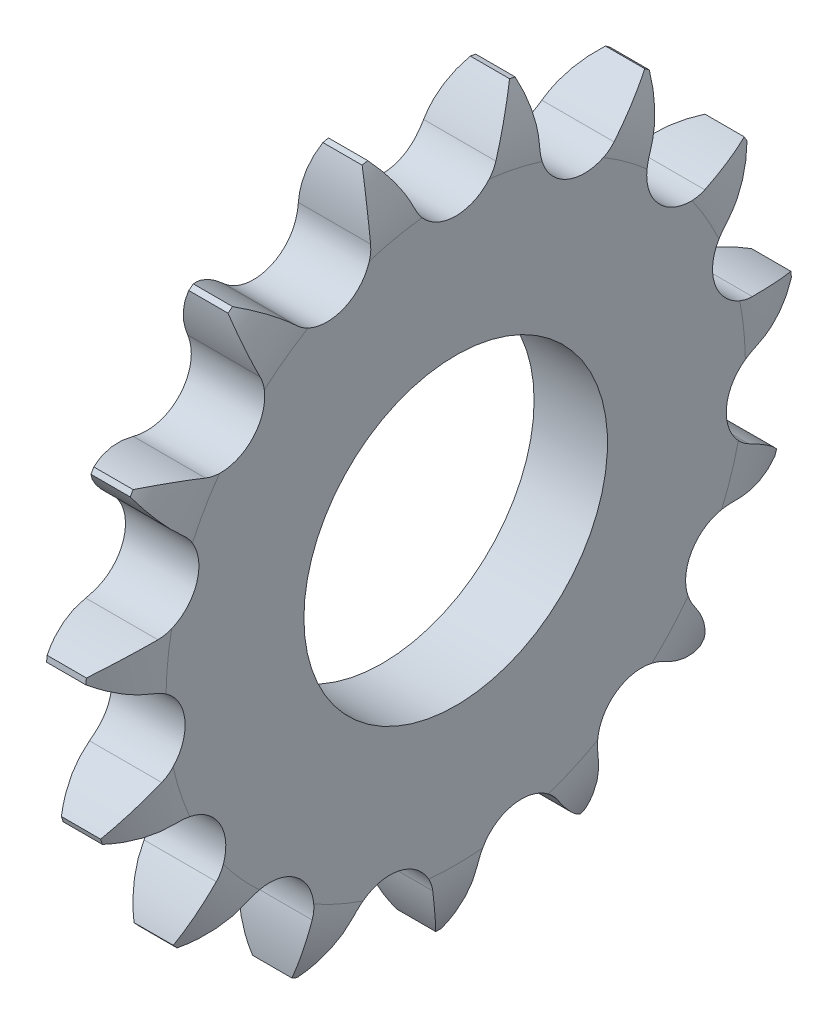
SolidWorks part; units mm, degrees
ref_plane "Plane1" through (0, 0, 0) normal (0, 0, 1) x (1, 0, 0)
ref_plane "Plane2" through (0, 0, 0) normal (0, 1, 0) x (1, 0, 0)
ref_plane "Plane3" through (0, 0, 0) normal (1, 0, 0) x (0, 0, -1)
sketch "Clipboard" plane through (0, 0, 0) normal (0, 1, 0) x (1, 0, 0)
  line L0 (0, 0) -> (9.2004, -2.4653)
  line L1 (-15, 0) -> (100, 0) construction
  line L2 (0, 0) -> (-0.8203, 0.9272)
  line L3 (0, 0) -> (-8.8973, 3.4006)
  line L4 (0, 0) -> (2.9944, 0.8023)
  line L5 (0, 0) -> (-46.8476, -17.4728)
  line L6 (0, 0) -> (-4.4098, -2.9753)
  line L7 (-0.8203, 0.9272) -> (47.2432, 14.7092)
  line L8 (-76.2, 38.1) -> (-72.9, 38.1)
  line L9 (-73.3242, 40.7328) -> (-72.926, 40.7699)
  line L10 (-73.4529, 9.1872) -> (-63.2129, 9.1872)
  circle A0 centre (0, 0) radius 3.175
  circle A1 centre (0, 0) radius 17.7306
  circle A2 centre (0, 0) radius 37.5
  dimension "Dr" = 6.35
  dimension "MHD" = 35.4612
  dimension "Hub_dia" = 75
  dimension "Num_teeth" = 15
  dimension "Pitch" = 9.525
  dimension "Width" = 3.1
  dimension "Side_relief" = 1.238
  dimension "Side_radius" = 9.525
  dimension "Overall_len" = 50
  dimension "Show_teeth" = 15
  dimension "Thickness" = 5.3196
  dimension "OAL" = 50.0005
  dimension "T_dim" = 3.3
  dimension "Fillet_rad" = 0.4
  dimension "Face_width" = 5.32
  dimension "Num_strands" = 1
  dimension "Transv_pitch" = 10.24
  dimension "Plate_wid" = 8.26
sketch "BasProSke" plane through (0, 0, 0) normal (0, 1, 0) x (1, 0, 0)
  line L0 (-10, 0) -> (60, 0) construction
  line L1 (0, 0) -> (0, 20.9886)
  line L2 (0, 0) -> (5.3196, 0)
  line L3 (5.3196, 0) -> (5.3196, 20.9886)
  line L4 (4.0816, 25.6845) -> (1.238, 25.6845)
  arc A0 (0, 20.9886) -> (1.238, 25.6845) centre (9.525, 20.9886) cw
  arc A1 (5.3196, 20.9886) -> (4.0816, 25.6845) centre (-4.2054, 20.9886) ccw
  dimension "Thickness" = 5.3196
  dimension "D1" = 9.525
  dimension "G1" = 1.238
  dimension "G2" = 1.238
  dimension "Diameter" = 51.369
revolve "Base-Revolve" add sketch "BasProSke" angle 360 about L0
sketch "TooCutSke" plane through (0, 0, 0) normal (1, 0, 0) x (0, 0, -1)
  line L0 (0, 22.9381) -> (2.9518, 21.6851) construction
  line L1 (0, 0) -> (0, 107) construction
  line L2 (0, 22.9381) -> (-10, 22.9381) construction
  line L3 (0, 22.9381) -> (-2.9518, 21.6851) construction
  arc A0 (2.9518, 21.6851) -> (5.5304, 25.5938) centre (14.876, 16.6236) cw
  arc A1 (2.9518, 21.6851) -> (-2.9518, 21.6851) centre (0, 22.9381) cw
  arc A2 (-2.9518, 21.6851) -> (-5.5304, 25.5938) centre (-14.876, 16.6236) ccw
  arc A3 (5.5304, 25.5938) -> (-5.5304, 25.5938) centre (0, 0) ccw
  dimension "R1" = 3.2067
  dimension "R2" = 12.954
  dimension "Overcut" = 26.1845
  dimension "Seat_radius" = 22.9381
  dimension "X" = 134
extrude "ToothCut" cut sketch "TooCutSke" along normal through all
pattern_circular "TeethCuts" count 15 every 24 about axis through (-10, 0, 0) along (1, 0, 0) of "ToothCut"
sketch "HubNeaOneSke" plane through (0, 0, 0) normal (-1, 0, 0) x (0, 0, 1)
  circle A0 centre (0, 0) radius 17.7306
  dimension "Diameter" = 35.4612
extrude "HubNearOne" [suppressed] add sketch "HubNeaOneSke" along normal blind 44.6809
fillet "HubNearOneFillet" [suppressed] radius 0.4
sketch "HubNeaBotSke" plane through (0, 0, 0) normal (-1, 0, 0) x (0, 0, 1)
  circle A0 centre (0, 0) radius 17.7306
  dimension "Diameter" = 35.4612
extrude "HubNearBoth" [suppressed] add sketch "HubNeaBotSke" along normal blind 22.3405
fillet "HubNearBothFillet" [suppressed] radius 0.4
ref_plane "FarPln" through (5.3196, 0, 0) normal (1, 0, 0) x (0, 0, -1)
sketch "HubFarSke" plane through (5.3196, 0, 0) normal (1, 0, 0) x (0, 0, -1)
  circle A0 centre (0, 0) radius 17.7306
  dimension "Diameter" = 35.4612
extrude "HubFar" [suppressed] add sketch "HubFarSke" along normal blind 22.3405
fillet "HubFarFillet" [suppressed] radius 0.4
sketch "BorSke" plane through (0, 0, 0) normal (1, 0, 0) x (0, 0, -1)
  circle A0 centre (0, 0) radius 11
  dimension "Diameter" = 22
extrude "Bore" cut sketch "BorSke" along normal mid plane 100.001
sketch "KeySke" plane through (0, 0, 0) normal (1, 0, 0) x (0, 0, -1)
  line L0 (-3, 0) -> (-3, 14.3)
  line L1 (-3, 14.3) -> (3, 14.3)
  line L2 (3, 14.3) -> (3, 0)
  line L3 (0, 0) -> (0, 34) construction
  line L4 (-3, 0) -> (3, 0)
  dimension "Offset" = 14.3
  dimension "Width" = 6
extrude "Keyway" [suppressed] cut sketch "KeySke" along normal mid plane 100.001
pattern_circular "Keyway2" [suppressed] count 2 every 90 about axis through (-10, 0, 0) along (1, 0, 0)
equation "' \"Pitch@Clipboard\" = 12.7"
equation "' \"Num_strands@Clipboard\" = 1"
equation "' \"Num_teeth@Clipboard\" = 9"
equation "' \"Hub_dia@Clipboard\" = 50"
equation "' \"Overall_len@Clipboard\" = 3"
equation "' \"Diameter@BorSke\" = 12"
equation "' \"T_dim@Clipboard\" = 1"
equation "' \"Width@KeySke\" = 2"
equation "' \"Dr@Clipboard\" = 8.51"
equation "' \"Face_width@Clipboard\" = 7.2"
equation "' \"Side_radius@Clipboard\" = 12.7"
equation "' \"Side_relief@Clipboard\" = 1.27"
equation "' \"Transv_pitch@Clipboard\" = 13.92"
equation "' \"Show_teeth@Clipboard\" = 9"
equation "' \"Fillet_rad@Clipboard\" = 0.6"
equation "' \"Plate_wid@Clipboard\" = 11.8"
equation "\"Num_teeth@Clipboard\" = int( \"Num_teeth@Clipboard\" )"
equation "\"Num_teeth@Clipboard\" = ((sgn( \"Num_teeth@Clipboard\" - 5.0)+1)*( \"Num_teeth@Clipboard\" - 5.0))/2 +5.0"
equation "\"Num_teeth@Clipboard\" = ((sgn( \"Num_teeth@Clipboard\" - 200.0)-1)*( \"Num_teeth@Clipboard\" - 200.0))/-2 +200.0"
equation "\"MHD@Clipboard\" = \"Pitch@Clipboard\" * (1.0 / tan(3.14159265 / \"Num_teeth@Clipboard\" )) - 1.04 * \"Plate_wid@Clipboard\" - 0.76"
equation "\"Thickness@Clipboard\"  = \"Face_width@Clipboard\" + (\"Num_strands@Clipboard\" - 1) * \"Transv_pitch@Clipboard\""
equation "\"OAL@Clipboard\" = \"Thickness@Clipboard\" + 2 * \"Fillet_rad@Clipboard\" + 1"
equation "\"MHD@Clipboard\" = ((sgn( \"MHD@Clipboard\" - \"Hub_dia@Clipboard\" )-1)*( \"MHD@Clipboard\" - \"Hub_dia@Clipboard\" ))/-2+ \"Hub_dia@Clipboard\""
equation "\"OAL@Clipboard\" = ((sgn( \"OAL@Clipboard\" - \"Overall_len@Clipboard\" )+1)*( \"OAL@Clipboard\" - \"Overall_len@Clipboard\" ))/2 + \"Overall_len@Clipboard\" + 0.0005"
equation "\"Num_teeth@TeethCuts\" = int( \"Show_teeth@Clipboard\" ) + 1"
equation "\"Num_teeth@TeethCuts\" = ((sgn( \"Num_teeth@TeethCuts\" - \"Num_teeth@Clipboard\" )-1)*( \"Num_teeth@TeethCuts\" - \"Num_teeth@Clipboard\" ))/-2+ \"Num_teeth@Clipboard\""
equation "\"Num_teeth@TeethCuts\" = ((sgn( \"Num_teeth@TeethCuts\" - 2.0)+1)*( \"Num_teeth@TeethCuts\" - 2.0))/2 +2.0"
equation "\"Angle@TeethCuts\" = 360.0 / \"Num_teeth@Clipboard\""
equation "\"Seat_radius@TooCutSke\" = ( \"Pitch@Clipboard\" / 2.0) / sin(3.14159265 / \"Num_teeth@Clipboard\" ) - \"Dr@Clipboard\" / 2.0 + \"Dr@Clipboard\" * 0.505"
equation "\"R1@TooCutSke\"  = \"Dr@Clipboard\" * 0.505"
equation "\"X@TooCutSke\" = 140.0 - (90.0 / \"Num_teeth@Clipboard\")"
equation "\"R2@TooCutSke\" = 0.12 * \"Dr@Clipboard\" * ( \"Num_teeth@Clipboard\" + 2.0)"
equation "\"Overcut@TooCutSke\" = 0.5 + 0.625 * \"Pitch@Clipboard\" - 0.5 * \"Dr@Clipboard\"  +  \"Pitch@Clipboard\" / 2.0 / sin(3.14159265 / \"Num_teeth@Clipboard\" )"
equation "\"Diameter@BasProSke\" = 2.0 * ( 0.625 * \"Pitch@Clipboard\" - 0.5 * \"Dr@Clipboard\"  +  \"Pitch@Clipboard\" / 2.0 / sin(3.14159265 / \"Num_teeth@Clipboard\" ))"
equation "\"Thickness@BasProSke\"  = \"Thickness@Clipboard\""
equation "\"G1@BasProSke\" =  \"Side_relief@Clipboard\""
equation "\"G2@BasProSke\" =  \"Side_relief@Clipboard\""
equation "\"D1@BasProSke\" =  \"Side_radius@Clipboard\""
equation "\"Diameter@HubNeaOneSke\" = \"MHD@Clipboard\""
equation "\"Length@HubNearOne\" = \"OAL@Clipboard\" - \"Thickness@BasProSke\""
equation "\"Diameter@HubNeaBotSke\" = \"MHD@Clipboard\""
equation "\"Length@HubNearBoth\" = ( \"OAL@Clipboard\" - \"Thickness@BasProSke\" ) / 2.0"
equation "\"D1@HubNearOneFillet\" = \"Fillet_rad@Clipboard\""
equation "\"D1@HubNearBothFillet\" = \"Fillet_rad@Clipboard\""
equation "\"Thickness@FarPln\" = \"Thickness@BasProSke\""
equation "\"Diameter@HubFarSke\" = \"MHD@Clipboard\""
equation "\"Length@HubFar\" = ( \"OAL@Clipboard\" - \"Thickness@BasProSke\" ) / 2.0"
equation "\"D1@HubFarFillet\" = \"Fillet_rad@Clipboard\""
equation "\"D1@Bore\" = \"OAL@Clipboard\" * 2.0"
equation "\"D1@Keyway\" = \"OAL@Clipboard\" * 2.0"
equation "\"Offset@KeySke\" = \"T_dim@Clipboard\" + \"Diameter@BorSke\" / 2.0"
